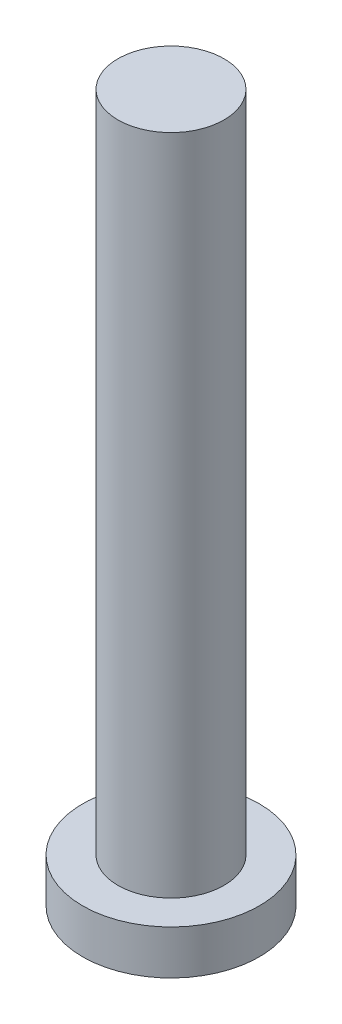
SolidWorks part; units mm, degrees
ref_plane "Front Plane" through (0, 0, 0) normal (0, 0, 1) x (1, 0, 0)
ref_plane "Top Plane" through (0, 0, 0) normal (0, 1, 0) x (1, 0, 0)
ref_plane "Right Plane" through (0, 0, 0) normal (1, 0, 0) x (0, 0, -1)
sketch "Sketch1" plane through (0, 0, 0) normal (0, 1, 0) x (1, 0, 0)
  circle A0 centre (0, 0) radius 2
  dimension "D1" = 4
extrude "Boss-Extrude1" add sketch "Sketch1" along normal blind 1
sketch "Sketch2" plane through (0, 1, 0) normal (0, 1, 0) x (1, 0, 0)
  circle A0 centre (0, 0) radius 1.2
  dimension "D1" = 2.4
extrude "Boss-Extrude2" add sketch "Sketch2" along normal blind 15
